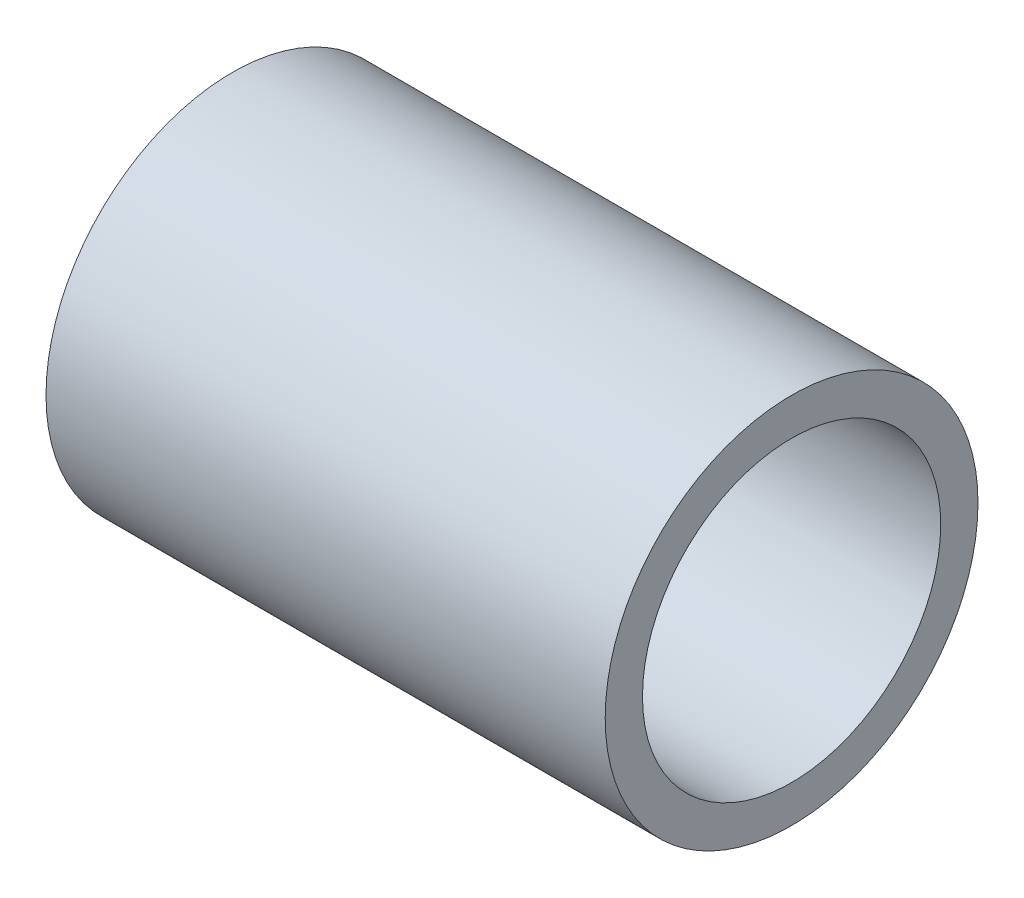
SolidWorks part; units mm, degrees
ref_plane "Alzado" through (0, 0, 0) normal (0, 0, 1) x (1, 0, 0)
ref_plane "Planta" through (0, 0, 0) normal (0, 1, 0) x (1, 0, 0)
ref_plane "Vista lateral" through (0, 0, 0) normal (1, 0, 0) x (0, 0, -1)
sketch "Croquis1" plane through (0, 0, 0) normal (1, 0, 0) x (0, 0, -1)
  circle A0 centre (0, 0) radius 4
  circle A1 centre (0, 0) radius 5
  dimension "D1" = 8
  dimension "D2" = 10
extrude "Saliente-Extruir1" add sketch "Croquis1" along normal blind 15
